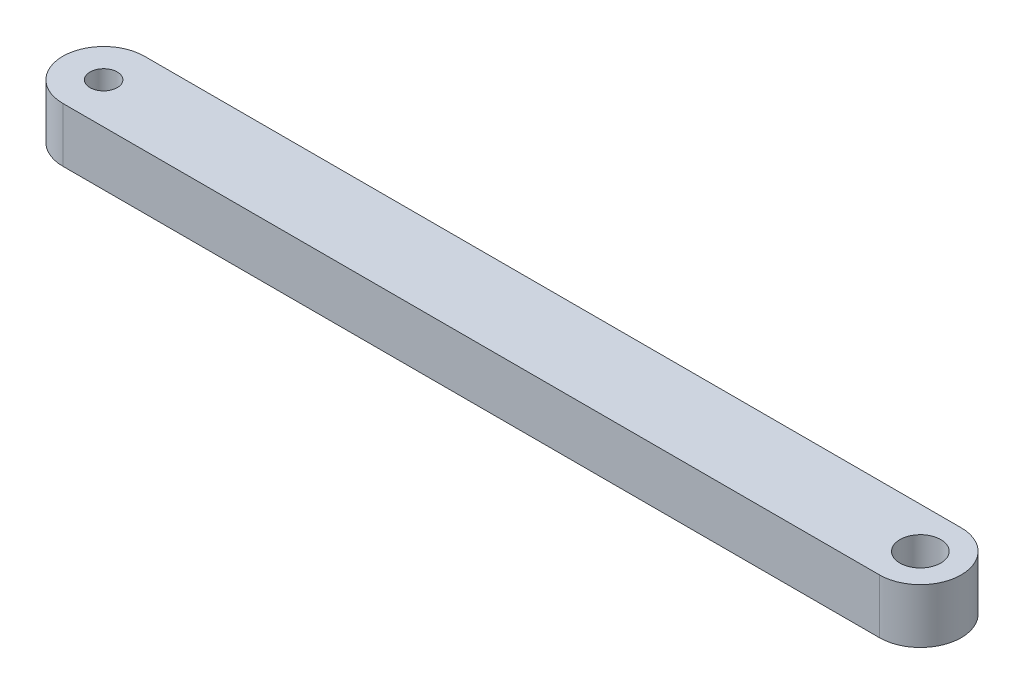
SolidWorks part; units mm, degrees
ref_plane "前视基准面" through (0, 0, 0) normal (0, 0, 1) x (1, 0, 0)
ref_plane "上视基准面" through (0, 0, 0) normal (0, 1, 0) x (1, 0, 0)
ref_plane "右视基准面" through (0, 0, 0) normal (1, 0, 0) x (0, 0, -1)
other "Configuration Table"
sketch "草图1" plane through (0, 0, 0) normal (0, 1, 0) x (1, 0, 0)
  line L0 (0, 3) -> (0, -3) construction
  line L1 (-30, 3) -> (30, 3)
  line L2 (-30, -3) -> (30, -3)
  line L3 (30, 3) -> (30, -3) construction
  arc A0 (-30, 3) -> (-30, -3) centre (-30, 0) ccw
  circle A5 centre (-30, 0) radius 1
  circle A6 centre (30, 0) radius 1.5
  arc A7 (30, -3) -> (30, 3) centre (30, 0) ccw
  point P4 (0, 0)
  point P7 (0, 3)
  point P10 (0, -3)
  dimension "D3" = 2
  dimension "D4" = 3
  dimension "D2" = 3
  dimension "D1" = 60
extrude "凸台-拉伸1" add sketch "草图1" along normal blind 4
